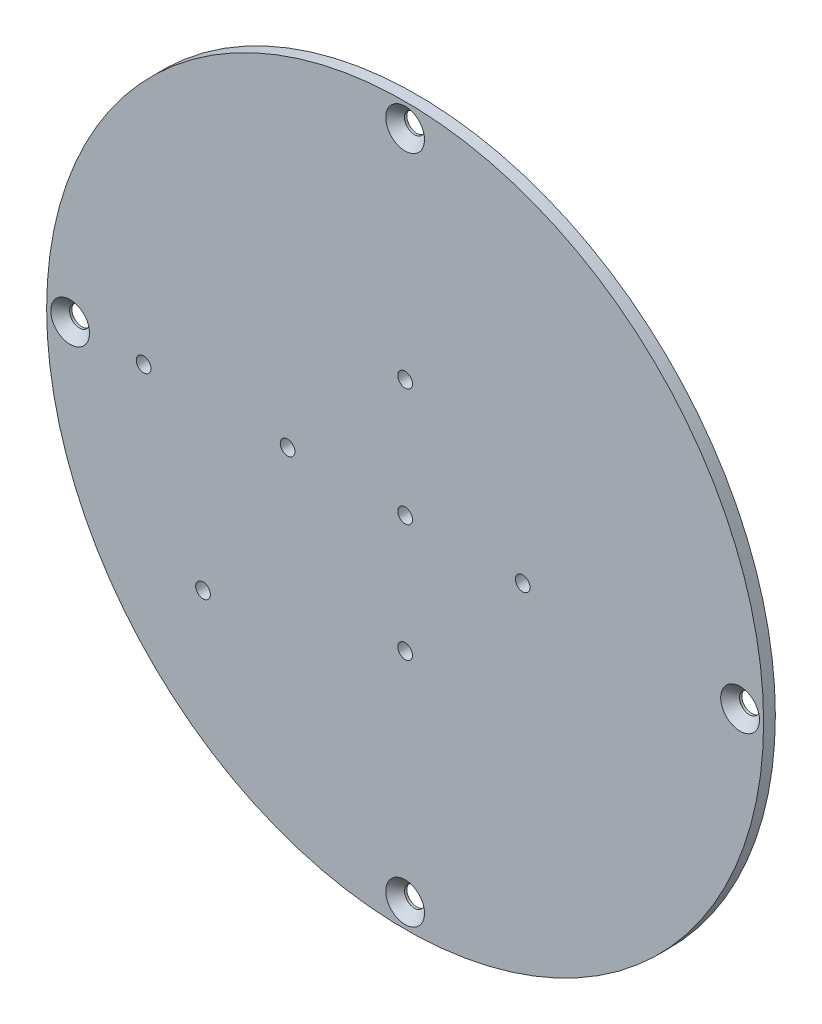
SolidWorks part; units mm, degrees
material "Cast Alloy Steel"
ref_plane "前视" through (0, 0, 0) normal (0, 0, 1) x (1, 0, 0)
ref_plane "上视" through (0, 0, 0) normal (0, 1, 0) x (1, 0, 0)
ref_plane "右视" through (0, 0, 0) normal (1, 0, 0) x (0, 0, -1)
sketch "草图1" plane through (0, 0, 0) normal (0, 0, 1) x (1, 0, 0)
  circle A0 centre (0, 0) radius 61
  dimension "D1" = 122
extrude "凸台-拉伸1" add sketch "草图1" along normal blind 2
hole_wizard "打孔尺寸(%根据十字)槽半沉头木螺钉的类型1" positions "草图2" profile "草图3" countersink size "M3" standard "GB" end condition through all
sketch "草图2" plane through (0, 0, 2) normal (0, 0, 1) x (1, 0, 0)
  point P0 (0, 57)
  dimension "D1" = 57
sketch "草图3" plane through (0, 57, 2) normal (1, 0, 0) x (0, -1, 0)
  line L0 (0, 0) -> (0, 2)
  line L1 (0, 2) -> (1.7, 2)
  line L2 (1.7, 2) -> (1.7, 1.6)
  line L3 (1.7, 1.6) -> (3.3, 0)
  line L5 (3.3, 0) -> (0, 0)
  line L6 (-1.7, 1.6) -> (-3.3, 0) construction
  line L11 (0, -6.35) -> (0, 107.95) construction
  dimension "通孔孔直径" = 3.4
  dimension "通孔孔深度" = 2
  dimension "近端锥形沉头孔直径" = 6.6
  dimension "近端锥形沉头孔角度" = 90
pattern_circular "阵列(圆周)1" count 4 over 360 about axis through (0, 0, 0) along (0, 0, 1) of "打孔尺寸(%根据十字)槽半沉头木螺钉的类型1"
sketch "草图4" plane through (0, 0, 2) normal (0, 0, 1) x (1, 0, 0)
  line L0 (0, 0) -> (54.4545, -19.8198) construction
  line L1 (0, 0) -> (57, 0) construction
  line L2 (27.2273, -9.9099) -> (50.9457, -18.5427) construction
  line L3 (28.5953, -6.1511) -> (52.3138, -14.784)
  line L4 (25.8592, -13.6687) -> (49.5777, -22.3015)
  arc A0 (28.5953, -6.1511) -> (25.8592, -13.6687) centre (27.2273, -9.9099) ccw
  arc A1 (49.5777, -22.3015) -> (52.3138, -14.784) centre (50.9457, -18.5427) ccw
  point P7 (39.0865, -14.2263)
  dimension "D1" = 20
  dimension "D2" = 8
extrude "切除-拉伸1" [suppressed] cut sketch "草图4" against normal through all
hole_wizard "M3 螺纹孔1" positions "草图5" profile "草图6" tap size "M3" standard "GB" end condition up to next
sketch "草图5" plane through (0, 0, 0) normal (0, 0, -1) x (-1, 0, 0)
  point P0 (-20, 0)
  dimension "D1" = 20
sketch "草图6" plane through (20, 0, 0) normal (1, 0, 0) x (0, 1, 0)
  line L0 (0, 0) -> (0, 2.001)
  line L1 (0, 2.001) -> (1.25, 2.001)
  line L2 (1.25, 2.001) -> (1.25, 0)
  line L5 (1.25, 0) -> (0, 0)
  line L11 (0, -6.35) -> (0, 107.95) construction
  dimension "通孔螺纹孔钻头直径" = 2.5
  dimension "通孔螺纹孔钻头深度" = 2.001
cosmetic thread "孔螺蚊线1" parameters "D2"=3
pattern_circular "阵列(圆周)2" count 4 over 360 about axis through (0, 0, 0) along (0, 0, 1) of "M3 螺纹孔1"
hole_wizard "M3 螺纹孔2" positions "草图7" profile "草图8" tap size "M3" standard "GB" end condition up to next
sketch "草图7" plane through (0, 0, 0) normal (0, 0, -1) x (-1, 0, 0)
  point P0 (0, 0)
sketch "草图8" plane through (0, 0, 0) normal (1, 0, 0) x (0, 1, 0)
  line L0 (0, 0) -> (0, 2)
  line L1 (0, 2) -> (1.25, 2)
  line L2 (1.25, 2) -> (1.25, 0)
  line L5 (1.25, 0) -> (0, 0)
  line L11 (0, -6.35) -> (0, 107.95) construction
  dimension "通孔螺纹孔钻头直径" = 2.5
  dimension "通孔螺纹孔钻头深度" = 2
cosmetic thread "孔螺蚊线2" parameters "D2"=3
hole_wizard "M3 螺纹孔3" positions "草图9" profile "草图10" tap size "M3" standard "GB" end condition through all
sketch "草图9" plane through (0, 0, 0) normal (0, 0, -1) x (-1, 0, 0)
  line L0 (44.5, 0) -> (0, 0) construction
  line L1 (0, 0) -> (34.3876, -28.2443) construction
  point P0 (34.3876, -28.2443)
  point P3 (44.5, 0)
  dimension "D1" = 44.5
  dimension "D2" = 30
sketch "草图10" plane through (-34.3876, -28.2443, 0) normal (1, 0, 0) x (0, 1, 0)
  line L0 (0, 0) -> (0, 2)
  line L1 (0, 2) -> (1.25, 2)
  line L2 (1.25, 2) -> (1.25, 0)
  line L5 (1.25, 0) -> (0, 0)
  line L11 (0, -6.35) -> (0, 107.95) construction
  dimension "通孔螺纹孔钻头直径" = 2.5
  dimension "通孔螺纹孔钻头深度" = 2
cosmetic thread "孔螺蚊线3" parameters "D2"=3
cosmetic thread "孔螺蚊线4" parameters "D2"=3
